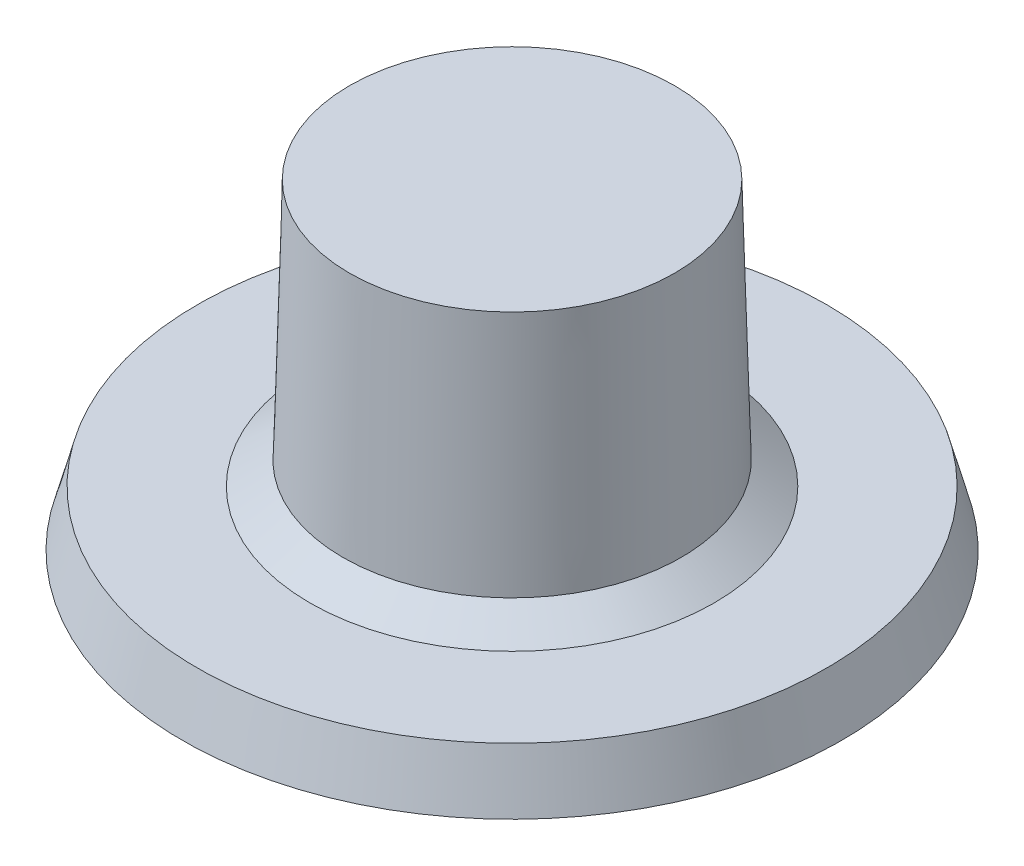
SolidWorks part; units mm, degrees
ref_plane "Front Plane" through (0, 0, 0) normal (0, 0, 1) x (1, 0, 0)
ref_plane "Top Plane" through (0, 0, 0) normal (0, 1, 0) x (1, 0, 0)
ref_plane "Right Plane" through (0, 0, 0) normal (1, 0, 0) x (0, 0, -1)
sketch "Sketch1" plane through (0, 0, 0) normal (1, 0, 0) x (0, 0, -1)
  line L0 (0, 0) -> (-82.7799, 0)
  line L1 (-82.7799, 0) -> (-79.0501, 13.8915)
  line L2 (-79.0501, 13.8915) -> (-50.7563, 13.8915)
  line L3 (-50.7563, 13.8915) -> (-42.4919, 19.6649)
  line L4 (-42.4919, 19.6649) -> (-40.8193, 80.6597)
  line L5 (-40.8193, 80.6597) -> (0, 80.6597)
  line L6 (0, 0) -> (0, 41.8031) construction
revolve "Revolve-Thin1" add sketch "Sketch1" angle 360 about L6
